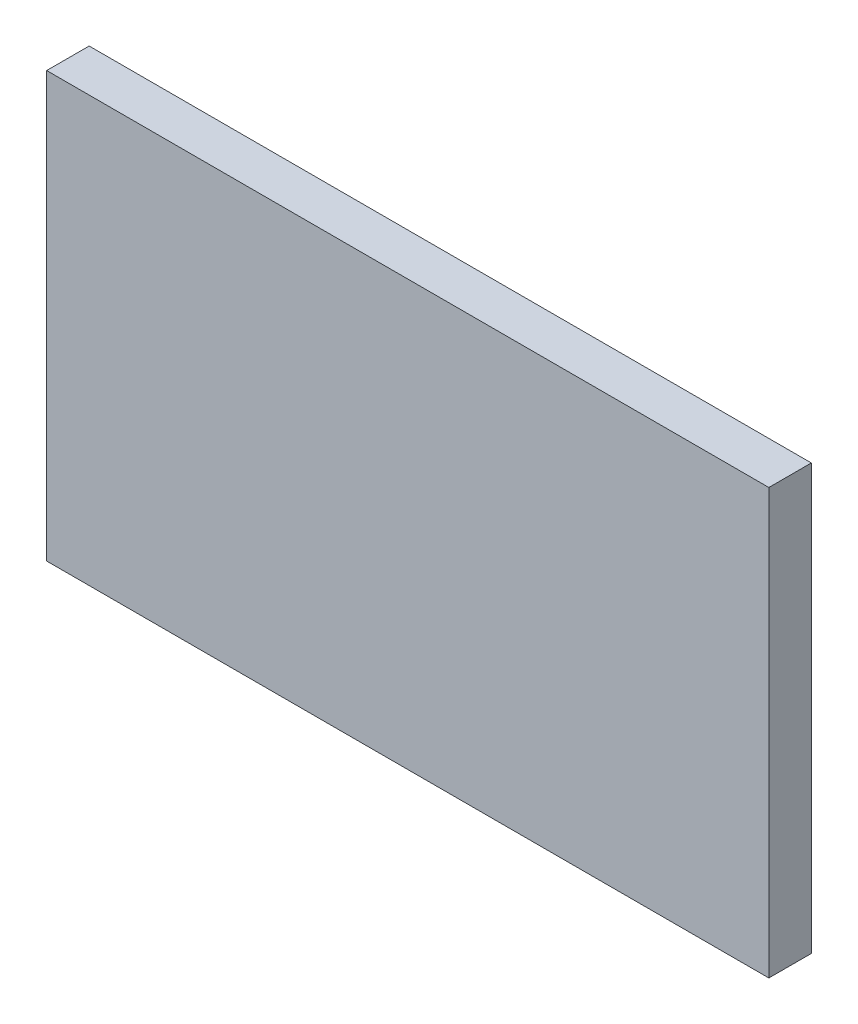
SolidWorks part; units mm, degrees
ref_plane "Front Plane" through (0, 0, 0) normal (0, 0, 1) x (1, 0, 0)
ref_plane "Top Plane" through (0, 0, 0) normal (0, 1, 0) x (1, 0, 0)
ref_plane "Right Plane" through (0, 0, 0) normal (1, 0, 0) x (0, 0, -1)
sketch "Sketch1" plane through (0, 0, 0) normal (0, 0, 1) x (1, 0, 0)
  line L1 (-53.975, 31.75) -> (53.975, 31.75)
  line L2 (-53.975, 31.75) -> (-53.975, -31.75)
  line L3 (-53.975, -31.75) -> (53.975, -31.75)
  line L4 (53.975, 31.75) -> (53.975, -31.75)
  line L5 (-53.975, 31.75) -> (53.975, -31.75) construction
  line L6 (-53.975, -31.75) -> (53.975, 31.75) construction
  point P0 (0, 0)
  dimension "D1" = 107.95
  dimension "D2" = 63.5
extrude "Boss-Extrude1" add sketch "Sketch1" along normal blind 6.35
